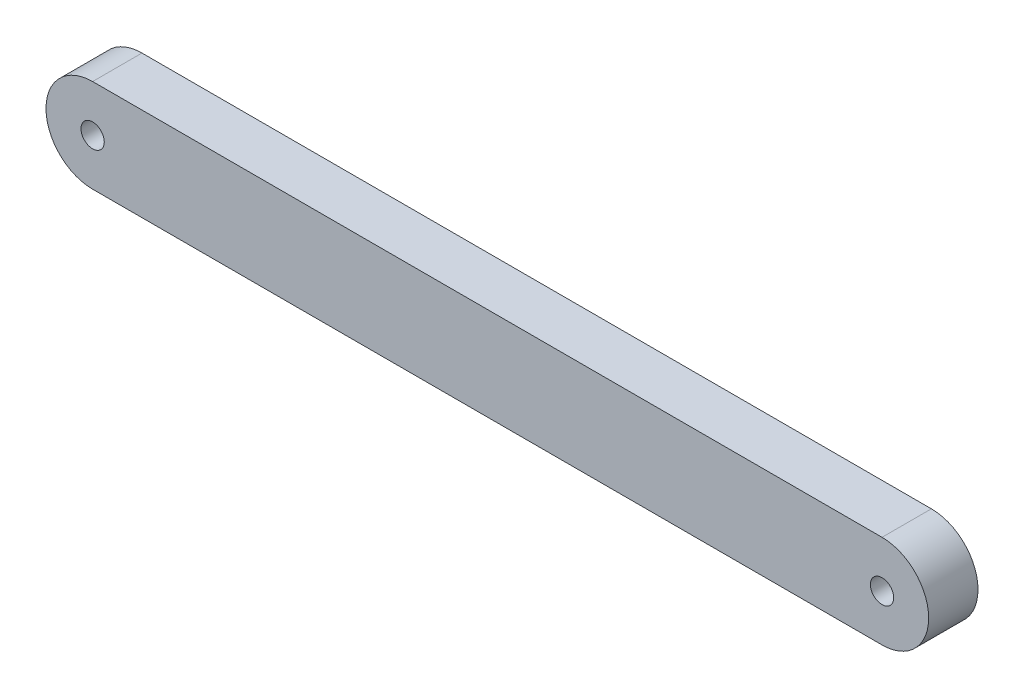
SolidWorks part; units mm, degrees
ref_plane "Plan de face" through (0, 0, 0) normal (0, 0, 1) x (1, 0, 0)
ref_plane "Plan de dessus" through (0, 0, 0) normal (0, 1, 0) x (1, 0, 0)
ref_plane "Plan de droite" through (0, 0, 0) normal (1, 0, 0) x (0, 0, -1)
sketch "Esquisse1" plane through (0, 0, 0) normal (0, 0, 1) x (1, 0, 0)
  line L0 (0, 0) -> (101.6, 0) construction
  line L1 (0, 6) -> (101.6, 6)
  line L2 (0, -6) -> (101.6, -6)
  arc A0 (0, 6) -> (0, -6) centre (0, 0) ccw
  arc A1 (101.6, -6) -> (101.6, 6) centre (101.6, 0) ccw
  point P3 (50.8, 0)
  dimension "D2" = 6
  dimension "D1" = 101.6
extrude "Boss.-Extru.1" add sketch "Esquisse1" along normal blind 6.35
sketch "Esquisse2" plane through (0, 0, 6.35) normal (0, 0, 1) x (1, 0, 0)
  circle A0 centre (0, 0) radius 1.5
  dimension "D1" = 3
extrude "Enlèv. mat.-Extru.1" cut sketch "Esquisse2" against normal blind 6.35 contours A0
sketch "Esquisse3" plane through (0, 0, 6.35) normal (0, 0, 1) x (1, 0, 0)
  circle A0 centre (101.6, 0) radius 1.5
extrude "Enlèv. mat.-Extru.2" cut sketch "Esquisse3" against normal blind 6.35
